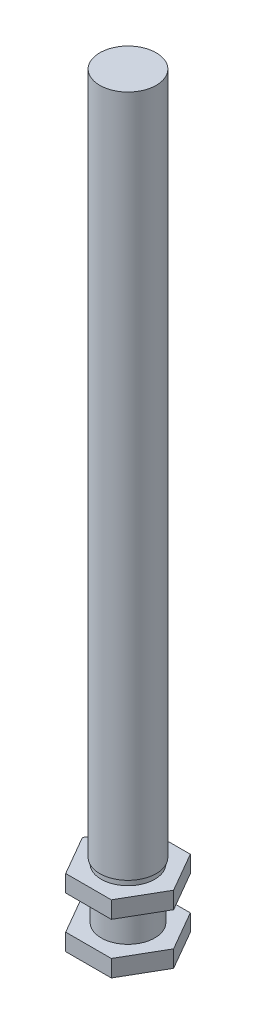
SolidWorks part; units mm, degrees
ref_plane "Front Plane" through (0, 0, 0) normal (0, 0, 1) x (1, 0, 0)
ref_plane "Top Plane" through (0, 0, 0) normal (0, 1, 0) x (1, 0, 0)
ref_plane "Right Plane" through (0, 0, 0) normal (1, 0, 0) x (0, 0, -1)
ref_plane "Plane1" through (0, 72.5, 0) normal (0, 1, 0) x (1, 0, 0)
sketch "Sketch1" plane through (0, 72.5, 0) normal (0, 1, 0) x (1, 0, 0)
  circle A0 centre (0, -26) radius 4.75
extrude "Boss-Extrude1" add sketch "Sketch1" along normal blind 14
ref_plane "Plane2" through (0, 73.5, 0) normal (0, 1, 0) x (1, 0, 0)
sketch "Sketch2" plane through (0, 73.5, 0) normal (0, 1, 0) x (1, 0, 0)
  line L1 (8.0829, -26) -> (4.0415, -19)
  line L2 (4.0415, -19) -> (-4.0415, -19)
  line L3 (-4.0415, -19) -> (-8.0829, -26)
  line L4 (-8.0829, -26) -> (-4.0415, -33)
  line L5 (-4.0415, -33) -> (4.0415, -33)
  line L6 (4.0415, -33) -> (8.0829, -26)
  circle A0 centre (0, -26) radius 7 construction
extrude "Boss-Extrude2" add sketch "Sketch2" along normal blind 3
ref_plane "Plane3" through (0, 82.5, 0) normal (0, 1, 0) x (1, 0, 0)
sketch "Sketch3" plane through (0, 82.5, 0) normal (0, 1, 0) x (1, 0, 0)
  line L1 (8.0829, -26) -> (4.0415, -19)
  line L2 (4.0415, -19) -> (-4.0415, -19)
  line L3 (-4.0415, -19) -> (-8.0829, -26)
  line L4 (-8.0829, -26) -> (-4.0415, -33)
  line L5 (-4.0415, -33) -> (4.0415, -33)
  line L6 (4.0415, -33) -> (8.0829, -26)
  circle A0 centre (0, -26) radius 7 construction
extrude "Boss-Extrude3" add sketch "Sketch3" along normal blind 3
ref_plane "Plane4" through (0, 86.5, 0) normal (0, 1, 0) x (1, 0, 0)
sketch "Sketch4" plane through (0, 86.5, 0) normal (0, 1, 0) x (1, 0, 0)
  circle A0 centre (0, -26) radius 5
extrude "Boss-Extrude4" add sketch "Sketch4" along normal blind 15
ref_plane "Plane5" through (0, 101.5, 0) normal (0, 1, 0) x (1, 0, 0)
sketch "Sketch5" plane through (0, 101.5, 0) normal (0, 1, 0) x (1, 0, 0)
  circle A0 centre (0, -26) radius 5
extrude "Boss-Extrude5" add sketch "Sketch5" along normal blind 106
